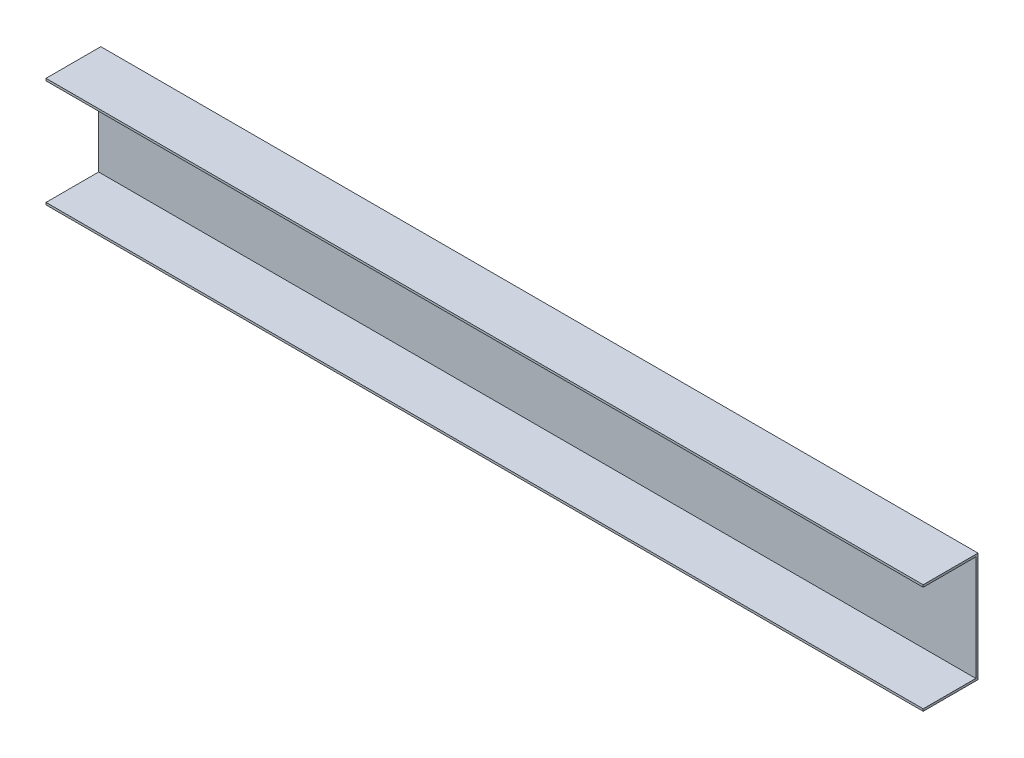
SolidWorks part; units mm, degrees
material "AISI 1020"
ref_plane "Alzado" through (0, 0, 0) normal (0, 0, 1) x (1, 0, 0)
ref_plane "Planta" through (0, 0, 0) normal (0, 1, 0) x (1, 0, 0)
ref_plane "Vista lateral" through (0, 0, 0) normal (1, 0, 0) x (0, 0, -1)
sketch "Croquis2" plane through (0, 0, 0) normal (1, 0, 0) x (0, 0, -1)
  line L0 (0, 50) -> (-50, 50)
  line L1 (0, -50) -> (0, 50)
  line L2 (0, -50) -> (-50, -50)
  point P2 (0, 0)
  dimension "D1" = 100
  dimension "D2" = 50
extrude "Extruir-Lámina1" add sketch "Croquis2" along normal blind 800 thin thin type one direction reverse wall 2
sketch3d "Croquis3D1" plane through (0, 0, 0) normal (0, 0, 1) x (1, 0, 0)
